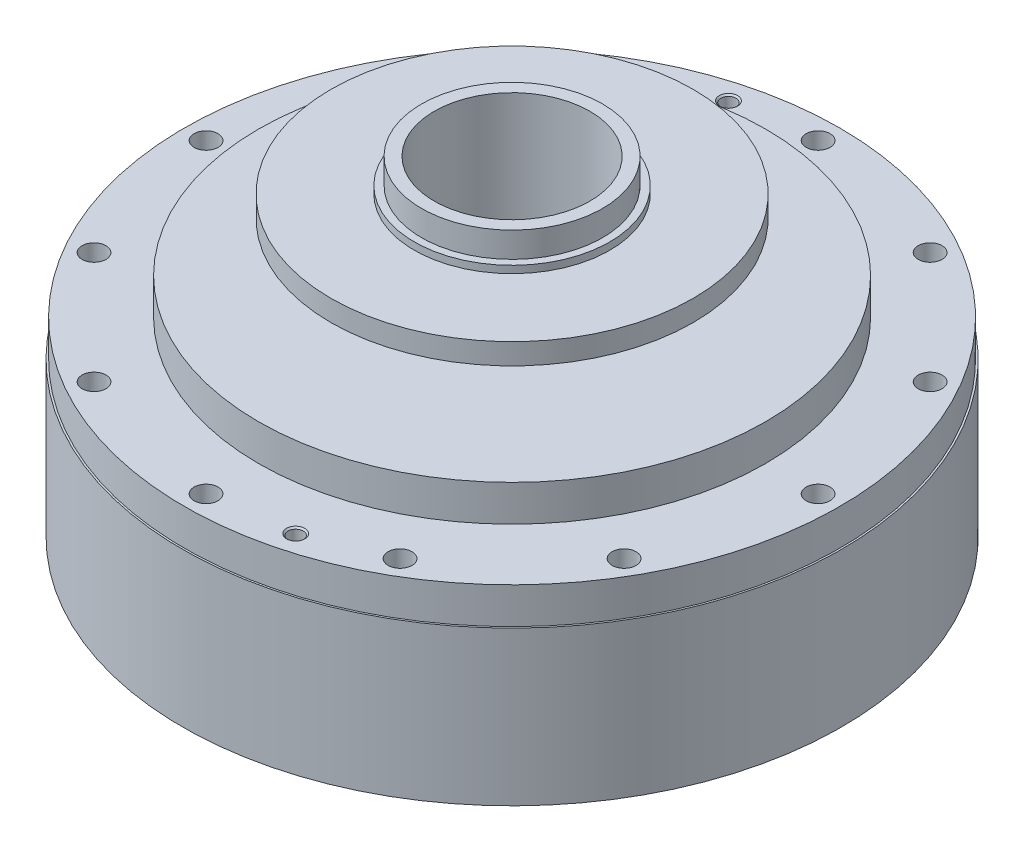
SolidWorks part; units mm, degrees
ref_plane "Front Plane" through (0, 0, 0) normal (0, 0, 1) x (1, 0, 0)
ref_plane "Top Plane" through (0, 0, 0) normal (0, 1, 0) x (1, 0, 0)
ref_plane "Right Plane" through (0, 0, 0) normal (1, 0, 0) x (0, 0, -1)
sketch "Sketch1" plane through (0, 0, 0) normal (1, 0, 0) x (0, 0, -1)
  line L0 (-33, 0) -> (-70, 0)
  line L1 (-70, 0) -> (-70, 5)
  line L2 (-70, 5) -> (-91, 5)
  line L3 (-91, 5) -> (-91, 47.5)
  line L4 (-91, 47.5) -> (-90.5, 47.5)
  line L5 (-90.5, 47.5) -> (-90.5, 57.5)
  line L6 (-90.5, 57.5) -> (-70, 57.5)
  line L7 (-70, 57.5) -> (-70, 67.5)
  line L8 (-70, 67.5) -> (-29.6, 67.5)
  line L9 (-29.6, 67.5) -> (-29.6, 81.2)
  line L10 (-29.6, 81.2) -> (-50, 81.2)
  line L11 (-50, 81.2) -> (-50, 87)
  line L12 (-50, 87) -> (-27, 87)
  line L26 (0, -94.12) -> (0, 155.7257) construction
  line L33 (-33, 9.2) -> (-33, 0)
  line L34 (-33, 9.2) -> (-23.5, 9.2)
  line L35 (-21.5, 96) -> (-25, 96)
  line L36 (-25, 96) -> (-25, 89)
  line L37 (-23.5, 9.2) -> (-23.5, 30)
  line L38 (-23.5, 30) -> (-21.5, 30)
  line L39 (-21.5, 30) -> (-21.5, 96)
  line L40 (-25, 89) -> (-27, 89)
  line L41 (-27, 89) -> (-27, 87)
  dimension "D2" = 43
  dimension "D3" = 47
  dimension "D4" = 66
  dimension "D5" = 140
  dimension "D6" = 182
  dimension "D7" = 100
  dimension "D8" = 29.5
  dimension "D9" = 50
  dimension "D10" = 10
  dimension "D11" = 57.5
  dimension "D12" = 67.5
  dimension "D13" = 140
  dimension "D14" = 181
  dimension "D15" = 5
  dimension "D16" = 9
  dimension "D17" = 59.2
  dimension "D18" = 9.2
  dimension "D19" = 5.8
  dimension "D20" = 54
  dimension "D21" = 2
revolve "Revolve1" add sketch "Sketch1" angle 360 about L26
sketch "Sketch3" plane through (0, 5, 0) normal (0, -1, 0) x (1, 0, 0)
  line L0 (0, 0) -> (-129.3834, 0) construction
  line L1 (-21.8702, -81.6207) -> (21.8702, 81.6207) construction
  line L2 (0, 0) -> (0, 84.5) construction
  circle A0 centre (0, 0) radius 84.5 construction
  circle A1 centre (-84.5, 0) radius 3.3
  circle A14 centre (-73.1791, 42.25) radius 3.3
  circle A15 centre (-42.25, 73.1791) radius 3.3
  circle A16 centre (0, 84.5) radius 3.3
  circle A17 centre (42.25, 73.1791) radius 3.3
  circle A18 centre (73.1791, 42.25) radius 3.3
  circle A19 centre (84.5, 0) radius 3.3
  circle A20 centre (73.1791, -42.25) radius 3.3
  circle A21 centre (42.25, -73.1791) radius 3.3
  circle A22 centre (0, -84.5) radius 3.3
  circle A23 centre (-42.25, -73.1791) radius 3.3
  circle A24 centre (-73.1791, -42.25) radius 3.3
  circle A25 centre (21.8702, 81.6207) radius 2.5 construction
  circle A26 centre (-21.8702, -81.6207) radius 2.5 construction
  point P31 (0, 0)
  point P34 (0, 0)
  dimension "D1" = 169
  dimension "D2" = 6.6
  dimension "D5" = 5
  dimension "D4" = 15
  dimension "D3" = 12
extrude "Cut-Extrude2" cut sketch "Sketch3" against normal through all
sketch "Sketch4" plane through (0, 0, 0) normal (0, -1, 0) x (1, 0, 0)
  line L0 (0, 0) -> (-35.2172, -131.4324) construction
  line L1 (-21.8702, -81.6207) -> (21.8702, 81.6207) construction
  circle A0 centre (0, 0) radius 58 construction
  circle A2 centre (-15.0115, -56.0237) radius 4 construction
  circle A17 centre (-50.2295, -29) radius 4 construction
  circle A18 centre (-56.0237, 15.0115) radius 4 construction
  circle A19 centre (-29, 50.2295) radius 4 construction
  circle A20 centre (15.0115, 56.0237) radius 4 construction
  circle A21 centre (50.2295, 29) radius 4 construction
  circle A22 centre (56.0237, -15.0115) radius 4 construction
  circle A23 centre (29, -50.2295) radius 4 construction
  point P23 (0, 0)
  dimension "D1" = 116
  dimension "D2" = 8
  dimension "D3" = 8
hole_wizard "M8 Tapped Hole1" positions "Sketch7" profile "Sketch8" tap size "M8" standard "ISO"
sketch "Sketch7" plane through (0, 0, 0) normal (0, -1, 0) x (-1, 0, 0)
  point P0 (15.0115, 56.0237)
  point P3 (-29, 50.2295)
  point P6 (-56.0237, 15.0115)
  point P9 (-50.2295, -29)
  point P12 (-15.0115, -56.0237)
  point P15 (29, -50.2295)
  point P18 (56.0237, -15.0115)
  point P21 (50.2295, 29)
sketch "Sketch8" plane through (-15.0115, 0, -56.0237) normal (1, 0, 0) x (0, 0, -1)
  line L0 (0, 0) -> (0, 25.7929)
  line L1 (0, 25.7929) -> (3.4, 23.75)
  line L2 (3.4, 23.75) -> (3.4, 0.625)
  line L3 (3.4, 0.625) -> (4.025, 0)
  line L5 (4.025, 0) -> (0, 0)
  line L6 (-3.4, 0.625) -> (-4.025, 0) construction
  line L10 (0, 25.7929) -> (-3.4, 23.75) construction
  line L11 (0, -6.35) -> (0, 107.95) construction
  dimension "Tap Drill Dia." = 6.8
  dimension "Tap Drill Depth" = 23.75
  dimension "Near C'Sink Dia." = 8.05
  dimension "Near C'Sink Angle" = 90
  dimension "Drill Angle" = 118
cosmetic thread "Hole Thread3" parameters "D1"=20, "D2"=8
cosmetic thread "Hole Thread4" parameters "D1"=20, "D2"=8
cosmetic thread "Hole Thread5" parameters "D1"=20, "D2"=8
cosmetic thread "Hole Thread6" parameters "D1"=20, "D2"=8
cosmetic thread "Hole Thread7" parameters "D1"=20, "D2"=8
cosmetic thread "Hole Thread8" parameters "D1"=20, "D2"=8
cosmetic thread "Hole Thread9" parameters "D1"=20, "D2"=8
cosmetic thread "Hole Thread10" parameters "D1"=20, "D2"=8
hole_wizard "M5x0.8 Tapped Hole2" positions "Sketch9" profile "Sketch10" tap size "M5x0.8" standard "ANSI Metric" end condition through all
sketch "Sketch9" plane through (0, 57.5, 0) normal (0, 1, 0) x (1, 0, 0)
  point P0 (-21.8702, 81.6207)
  point P3 (21.8702, -81.6207)
sketch "Sketch10" plane through (-21.8702, 57.5, -81.6207) normal (1, 0, 0) x (0, 0, 1)
  line L0 (0, 0) -> (0, 57.5)
  line L1 (0, 57.5) -> (2.1, 57.5)
  line L2 (2.1, 57.5) -> (2.1, 0.425)
  line L3 (2.1, 0.425) -> (2.525, 0)
  line L5 (2.525, 0) -> (0, 0)
  line L6 (-2.1, 0.425) -> (-2.525, 0) construction
  line L11 (0, -6.35) -> (0, 107.95) construction
  dimension "Thru Tap Drill Dia." = 4.2
  dimension "Thru Tap Drill Depth" = 57.5
  dimension "Near C'Sink Dia." = 5.05
  dimension "Near C'Sink Angle" = 90
cosmetic thread "Hole Thread11" parameters "D1"=20, "D2"=5
cosmetic thread "Hole Thread12" parameters "D1"=20, "D2"=5
sketch "Sketch12" plane through (0, 9.2, 0) normal (0, -1, 0) x (1, 0, 0)
  line L1 (-19.799, -19.799) -> (19.799, -19.799) construction
  line L2 (-19.799, -19.799) -> (-19.799, 19.799) construction
  line L3 (-19.799, 19.799) -> (19.799, 19.799) construction
  line L4 (19.799, -19.799) -> (19.799, 19.799) construction
  line L5 (-19.799, -19.799) -> (19.799, 19.799) construction
  line L6 (-19.799, 19.799) -> (19.799, -19.799) construction
  point P0 (0, 0)
  dimension "D1" = 56
hole_wizard "M4 Tapped Hole1" positions "3DSketch1" profile "Sketch13" tap size "M4" standard "ISO"
sketch3d "3DSketch1"
  point P0 (-19.799, 9.2, 19.799)
  point P3 (19.799, 9.2, 19.799)
  point P6 (19.799, 9.2, -19.799)
  point P8 (-19.799, 9.2, -19.799)
sketch "Sketch13" plane through (-19.799, 9.2, 19.799) normal (1, 0, 0) x (0, 0, -1)
  line L0 (0, 0) -> (0, 21.0914)
  line L1 (0, 21.0914) -> (1.65, 20.1)
  line L2 (1.65, 20.1) -> (1.65, 0.375)
  line L3 (1.65, 0.375) -> (2.025, 0)
  line L5 (2.025, 0) -> (0, 0)
  line L6 (-1.65, 0.375) -> (-2.025, 0) construction
  line L10 (0, 21.0914) -> (-1.65, 20.1) construction
  line L11 (0, -6.35) -> (0, 107.95) construction
  dimension "Tap Drill Dia." = 3.3
  dimension "Tap Drill Depth" = 20.1
  dimension "Near C'Sink Dia." = 4.05
  dimension "Near C'Sink Angle" = 90
  dimension "Drill Angle" = 118
cosmetic thread "Hole Thread13" parameters "D1"=18, "D2"=4
cosmetic thread "Hole Thread14" parameters "D1"=18, "D2"=4
cosmetic thread "Hole Thread15" parameters "D1"=18, "D2"=4
cosmetic thread "Hole Thread16" parameters "D1"=18, "D2"=4
